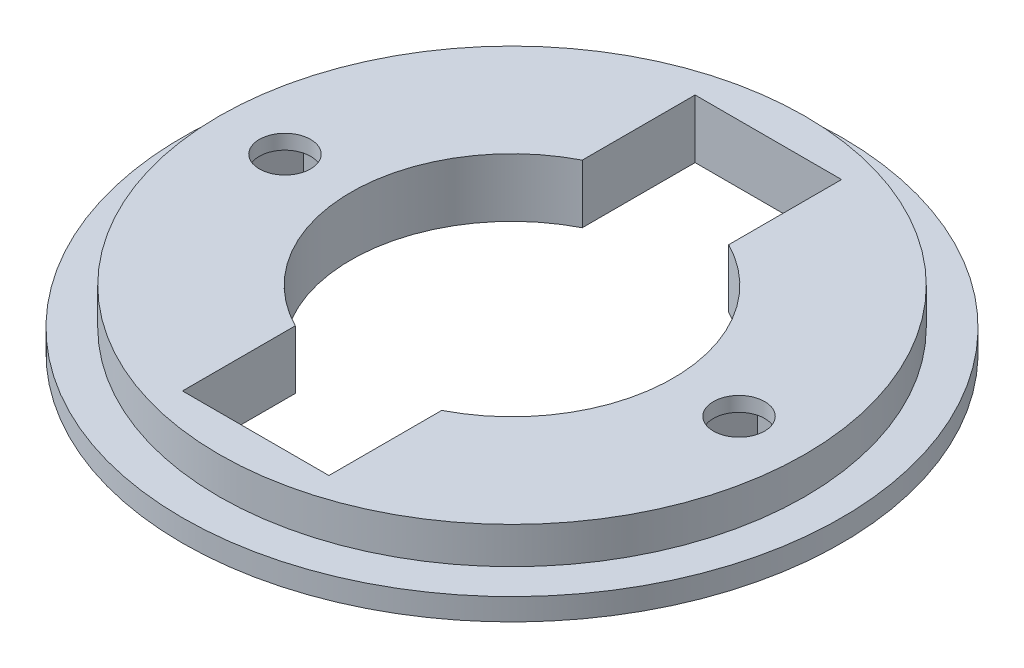
SolidWorks part; units mm, degrees
ref_plane "Front Plane" through (0, 0, 0) normal (0, 0, 1) x (1, 0, 0)
ref_plane "Top Plane" through (0, 0, 0) normal (0, 1, 0) x (1, 0, 0)
ref_plane "Right Plane" through (0, 0, 0) normal (1, 0, 0) x (0, 0, -1)
sketch "Sketch1" plane through (0, 0, 0) normal (0, 1, 0) x (1, 0, 0)
  circle A0 centre (0, 0) radius 22.5
  dimension "D1" = 45
extrude "Boss-Extrude2" add sketch "Sketch1" along normal blind 4
sketch "Sketch2" plane through (0, 4, 0) normal (0, 1, 0) x (1, 0, 0)
  circle A0 centre (0, 0) radius 20
  circle A1 centre (0, 0) radius 22.5
  dimension "D1" = 40
  dimension "D2" = 45
extrude "Cut-Extrude1" cut sketch "Sketch2" against normal blind 2.5
sketch "Sketch3" plane through (0, 4, 0) normal (0, 1, 0) x (1, 0, 0)
  line L0 (5, -9.798) -> (5, -17.5)
  line L1 (-5, 17.5) -> (5, 17.5)
  line L2 (-5, 17.5) -> (-5, 9.798)
  line L3 (-5, -17.5) -> (5, -17.5)
  line L4 (5, 17.5) -> (5, 9.798)
  line L5 (-5, 17.5) -> (5, -17.5) construction
  line L6 (-5, -17.5) -> (5, 17.5) construction
  line L7 (-5, -9.798) -> (-5, -17.5)
  arc A0 (-5, 9.798) -> (-5, -9.798) centre (0, 0) ccw
  arc A1 (5, -9.798) -> (5, 9.798) centre (0, 0) ccw
  point P0 (0, 0)
  dimension "D3" = 22
  dimension "D1" = 35
  dimension "D2" = 10
extrude "Cut-Extrude2" cut sketch "Sketch3" against normal through all
sketch "Sketch4" plane through (0, 4, 0) normal (0, 1, 0) x (1, 0, 0)
  line L0 (0, 0) -> (24.6184, 0) construction
  line L1 (0, 0) -> (0, -30.6196) construction
  circle A0 centre (15.5, 0) radius 1.75
  circle A3 centre (-15.5, 0) radius 1.75
  dimension "D1" = 3.5
  dimension "D3" = 31
extrude "Cut-Extrude3" cut sketch "Sketch4" against normal through all
sketch "Sketch5" plane through (0, 0, 0) normal (0, -1, 0) x (1, 0, 0)
  line L0 (0, 0) -> (-24.2775, 0) construction
  line L1 (0, 0) -> (0, 27.2098) construction
  line L2 (13.7679, -3) -> (12.0359, 0)
  line L3 (-12.0359, 0) -> (-13.7679, 3)
  line L4 (-13.7679, 3) -> (-17.2321, 3)
  line L5 (-17.2321, 3) -> (-18.9641, 0)
  line L6 (-18.9641, 0) -> (-17.2321, -3)
  line L7 (-17.2321, -3) -> (-13.7679, -3)
  line L8 (-13.7679, -3) -> (-12.0359, 0)
  line L9 (17.2321, -3) -> (13.7679, -3)
  line L10 (18.9641, 0) -> (17.2321, -3)
  line L11 (17.2321, 3) -> (18.9641, 0)
  line L12 (13.7679, 3) -> (17.2321, 3)
  line L13 (12.0359, 0) -> (13.7679, 3)
  circle A0 centre (-15.5, 0) radius 3 construction
  circle A1 centre (15.5, 0) radius 3 construction
  dimension "D1" = 6
extrude "Cut-Extrude4" cut sketch "Sketch5" against normal blind 3
